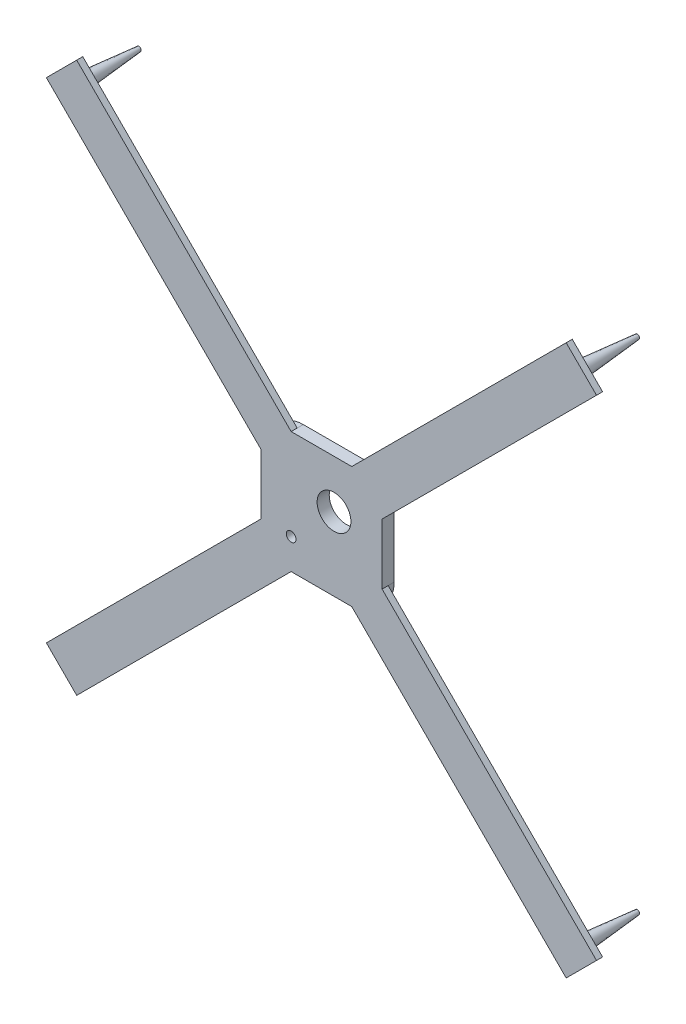
SolidWorks part; units mm, degrees
material "6061 Alloy"
ref_plane "Front" through (0, 0, 0) normal (0, 0, 1) x (1, 0, 0)
ref_plane "Top" through (0, 0, 0) normal (0, 1, 0) x (1, 0, 0)
ref_plane "Right" through (0, 0, 0) normal (1, 0, 0) x (0, 0, -1)
sketch "Sketch3" plane through (0, 0, 0) normal (0, 0, 1) x (1, 0, 0)
  line L1 (0, 0) -> (50.8, 0)
  line L2 (0, 0) -> (0, 50.8)
  line L3 (0, 50.8) -> (50.8, 50.8)
  line L4 (50.8, 0) -> (50.8, 50.8)
  dimension "D1" = 50.8
  dimension "D2" = 50.8
extrude "Boss-Extrude2" add sketch "Sketch3" along normal blind 5.08
sketch "Sketch4" plane through (0, 0, 5.08) normal (0, 0, 1) x (1, 0, 0)
  line L0 (0, 50.8) -> (0, 0) construction
  line L1 (0, 0) -> (50.8, 0) construction
  circle A0 centre (12.7, 12.7) radius 2.032
  dimension "D1" = 4.064
  dimension "D2" = 12.7
  dimension "D3" = 12.7
extrude "Cut-Extrude2" cut sketch "Sketch4" against normal through all
fillet "Fillet2" radius 12.7 4 edges at (0, 0, 2.54) (0, 50.8, 2.54) (50.8, 50.8, 2.54) (50.8, 0, 2.54)
sketch "Sketch5" plane through (0, 0, 5.08) normal (0, 0, 1) x (1, 0, 0)
  line L0 (127.9026, -89.8026) -> (38.1, 0)
  line L1 (50.8, 12.7) -> (38.1, 0)
  line L2 (127.9026, -89.8026) -> (140.6026, -77.1026)
  line L3 (140.6026, -77.1026) -> (50.8, 12.7)
  line L4 (-89.8026, -77.1026) -> (0, 12.7)
  line L5 (0, 12.7) -> (12.7, 0)
  line L6 (12.7, 0) -> (-77.1026, -89.8026)
  line L7 (-77.1026, -89.8026) -> (-89.8026, -77.1026)
  line L8 (0, 38.1) -> (-89.8026, 127.9026)
  line L9 (-89.8026, 127.9026) -> (-77.1026, 140.6026)
  line L10 (-77.1026, 140.6026) -> (12.7, 50.8)
  line L11 (12.7, 50.8) -> (0, 38.1)
  line L12 (50.8, 38.1) -> (140.6026, 127.9026)
  line L13 (38.1, 50.8) -> (127.9026, 140.6026)
  line L14 (127.9026, 140.6026) -> (140.6026, 127.9026)
  line L15 (50.8, 38.1) -> (38.1, 50.8)
  line L18 (50.8, 12.7) -> (50.8, 38.1) construction
  dimension "D1" = 135
  dimension "D2" = 127
extrude "Boss-Extrude3" add sketch "Sketch5" against normal blind 2.54
sketch "Sketch6" plane through (0, 0, 2.54) normal (0, 0, -1) x (-1, 0, 0)
  line L0 (-140.6026, 127.9026) -> (-127.9026, 140.6026) construction
  line L1 (-134.2526, 134.2526) -> (-129.7624, 129.7624) construction
  line L2 (78.9624, 129.7624) -> (83.4526, 134.2526) construction
  line L3 (77.1026, 140.6026) -> (89.8026, 127.9026) construction
  line L4 (78.9624, -78.9624) -> (83.4526, -83.4526) construction
  line L5 (89.8026, -77.1026) -> (77.1026, -89.8026) construction
  line L6 (-129.7624, -78.9624) -> (-134.2526, -83.4526) construction
  line L7 (-127.9026, -89.8026) -> (-140.6026, -77.1026) construction
  circle A0 centre (-129.7624, 129.7624) radius 3.175
  circle A1 centre (78.9624, 129.7624) radius 3.175
  circle A2 centre (78.9624, -78.9624) radius 3.175
  circle A3 centre (-129.7624, -78.9624) radius 3.175
  dimension "D1" = 6.35
  dimension "D3" = 6.35
  dimension "D5" = 6.35
  dimension "D2" = 6.35
  dimension "D4" = 6.35
extrude "Boss-Extrude4" add sketch "Sketch6" along normal blind 25.4 draft 5
sketch "Sketch7" plane through (0, 0, 5.08) normal (0, 0, 1) x (1, 0, 0)
  line L0 (12.7, 12.7) -> (30.6605, 30.6605) construction
  line L1 (0, 38.1) -> (0, 12.7) construction
  circle A0 centre (30.6605, 30.6605) radius 7.0818
  dimension "D1" = 25.4
  dimension "D2" = 45
extrude "Cut-Extrude3" cut sketch "Sketch7" against normal through all
